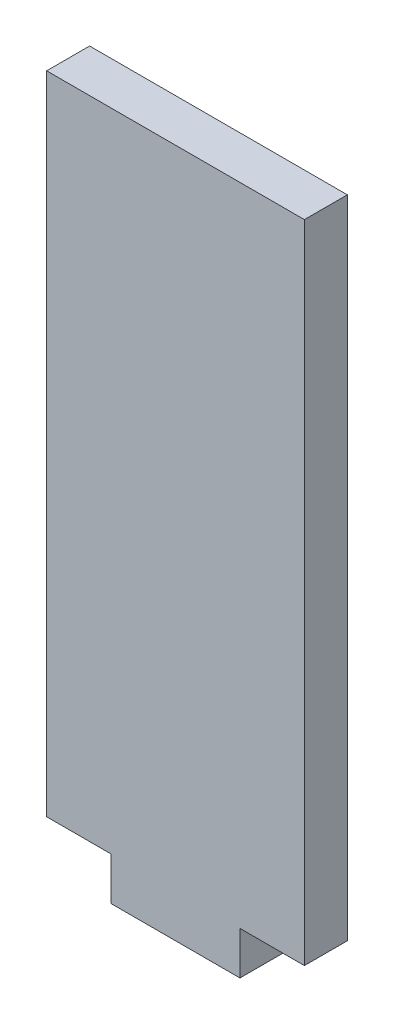
SolidWorks part; units mm, degrees
ref_plane "前视基准面" through (0, 0, 0) normal (0, 0, 1) x (1, 0, 0)
ref_plane "上视基准面" through (0, 0, 0) normal (0, 1, 0) x (1, 0, 0)
ref_plane "右视基准面" through (0, 0, 0) normal (1, 0, 0) x (0, 0, -1)
sketch "草图1" plane through (0, 0, 0) normal (0, 0, 1) x (1, 0, 0)
  line L0 (-6, 0) -> (-6, 15)
  line L1 (-6, 0) -> (-3, 0)
  line L3 (6, 0) -> (6, 15)
  line L4 (-3, 0) -> (-3, -2)
  line L6 (-3, -2) -> (3, -2)
  line L7 (3, 0) -> (3, -2)
  line L8 (-6, 15) -> (-6, 30.0788)
  line L9 (-6, 30.0788) -> (6, 30.0788)
  line L10 (6, 30.0788) -> (6, 15)
  line L11 (3, 0) -> (6, 0)
extrude "凸台-拉伸1" add sketch "草图1" along normal blind 2 contours L9 L10 L3 L11 L7 L6 L4 L1 L0 L8
sketch3d "3D草图1"
  spline S0 degree 3 poles (-3.7281, 8.6762, 2) (-3.7074, 8.1505, 2) (-3.6718, 7.893, 2) (-3.5521, 7.3881, 2) (-3.4667, 7.1383, 2) (-3.2501, 6.663, 2) (-3.1202, 6.4386, 2) (-2.8173, 6.0158, 2) (-2.6424, 5.8163, 2) (-2.2631, 5.461, 2) (-2.0574, 5.3028, 2) (-1.6134, 5.0266, 2) (-1.377, 4.9103, 2) (-0.8912, 4.7283, 2) (-0.6386, 4.661, 2) (-0.1203, 4.5774, 2) (0.1389, 4.5619, 2) (0.6578, 4.5819, 2) (0.9202, 4.6183, 2) (1.4267, 4.7412, 2) (1.6715, 4.827, 2) (2.1443, 5.0472, 2) (2.3719, 5.1823, 2) (2.7901, 5.4898, 2) (2.9836, 5.6635, 2) (3.3382, 6.0517, 2) (3.4938, 6.2605, 2) (3.7626, 6.7045, 2) (3.8768, 6.9427, 2) (4.0554, 7.4334, 2) (4.12, 7.6847, 2) (4.2005, 8.1988, 2) (4.2159, 8.4635, 2) (4.1957, 8.9828, 2) (4.1608, 9.2399, 2) (4.0405, 9.749, 2) (3.9551, 9.9981, 2) (3.7405, 10.4703, 2) (3.6101, 10.6966, 2) (3.3044, 11.1235, 2) (3.1331, 11.3188, 2) (2.7547, 11.674, 2) (2.545, 11.8354, 2) (2.1022, 12.1109, 2) (1.8696, 12.2256, 2) (1.3821, 12.4088, 2) (1.1259, 12.4769, 2) (0.6133, 12.5599, 2) (0.3541, 12.5761, 2) (-0.1701, 12.5562, 2) (-0.4295, 12.52, 2) (-0.9338, 12.3982, 2) (-1.1825, 12.3114, 2) (-1.6567, 12.0906, 2) (-1.88, 11.9582, 2) (-2.2993, 11.6505, 2) (-2.4966, 11.4732, 2) (-2.8474, 11.0893, 2) (-3.003, 10.8816, 2) (-3.2742, 10.4343, 2) (-3.388, 10.1968, 2) (-3.5658, 9.7094, 2) (-3.6314, 9.4564, 2) (-3.7128, 8.9374, 2) (-3.7281, 8.6762, 2) (-3.7074, 8.1505, 2) (-3.6718, 7.893, 2) knots -0.03125 -0.03125 0 0 0.03125 0.03125 0.0625 0.0625 0.09375 0.09375 0.125 0.125 0.15625 0.15625 0.1875 0.1875 0.21875 0.21875 0.25 0.25 0.28125 0.28125 0.3125 0.3125 0.34375 0.34375 0.375 0.375 0.40625 0.40625 0.4375 0.4375 0.46875 0.46875 0.5 0.5 0.53125 0.53125 0.5625 0.5625 0.59375 0.59375 0.625 0.625 0.65625 0.65625 0.6875 0.6875 0.71875 0.71875 0.75 0.75 0.78125 0.78125 0.8125 0.8125 0.84375 0.84375 0.875 0.875 0.90625 0.90625 0.9375 0.9375 0.96875 0.96875 1 1 1.03125 1.03125 1.0625 only from (-3.7177, 8.4134, 2) to (-3.7177, 8.4134, 2)
  spline S1 degree 3 poles (-3.7281, 8.6762, 2) (-3.7074, 8.1505, 2) (-3.6718, 7.893, 2) (-3.5521, 7.3881, 2) (-3.4667, 7.1383, 2) (-3.2501, 6.663, 2) (-3.1202, 6.4386, 2) (-2.8173, 6.0158, 2) (-2.6424, 5.8163, 2) (-2.2631, 5.461, 2) (-2.0574, 5.3028, 2) (-1.6134, 5.0266, 2) (-1.377, 4.9103, 2) (-0.8912, 4.7283, 2) (-0.6386, 4.661, 2) (-0.1203, 4.5774, 2) (0.1389, 4.5619, 2) (0.6578, 4.5819, 2) (0.9202, 4.6183, 2) (1.4267, 4.7412, 2) (1.6715, 4.827, 2) (2.1443, 5.0472, 2) (2.3719, 5.1823, 2) (2.7901, 5.4898, 2) (2.9836, 5.6635, 2) (3.3382, 6.0517, 2) (3.4938, 6.2605, 2) (3.7626, 6.7045, 2) (3.8768, 6.9427, 2) (4.0554, 7.4334, 2) (4.12, 7.6847, 2) (4.2005, 8.1988, 2) (4.2159, 8.4635, 2) (4.1957, 8.9828, 2) (4.1608, 9.2399, 2) (4.0405, 9.749, 2) (3.9551, 9.9981, 2) (3.7405, 10.4703, 2) (3.6101, 10.6966, 2) (3.3044, 11.1235, 2) (3.1331, 11.3188, 2) (2.7547, 11.674, 2) (2.545, 11.8354, 2) (2.1022, 12.1109, 2) (1.8696, 12.2256, 2) (1.3821, 12.4088, 2) (1.1259, 12.4769, 2) (0.6133, 12.5599, 2) (0.3541, 12.5761, 2) (-0.1701, 12.5562, 2) (-0.4295, 12.52, 2) (-0.9338, 12.3982, 2) (-1.1825, 12.3114, 2) (-1.6567, 12.0906, 2) (-1.88, 11.9582, 2) (-2.2993, 11.6505, 2) (-2.4966, 11.4732, 2) (-2.8474, 11.0893, 2) (-3.003, 10.8816, 2) (-3.2742, 10.4343, 2) (-3.388, 10.1968, 2) (-3.5658, 9.7094, 2) (-3.6314, 9.4564, 2) (-3.7128, 8.9374, 2) (-3.7281, 8.6762, 2) (-3.7074, 8.1505, 2) (-3.6718, 7.893, 2) knots -0.03125 -0.03125 0 0 0.03125 0.03125 0.0625 0.0625 0.09375 0.09375 0.125 0.125 0.15625 0.15625 0.1875 0.1875 0.21875 0.21875 0.25 0.25 0.28125 0.28125 0.3125 0.3125 0.34375 0.34375 0.375 0.375 0.40625 0.40625 0.4375 0.4375 0.46875 0.46875 0.5 0.5 0.53125 0.53125 0.5625 0.5625 0.59375 0.59375 0.625 0.625 0.65625 0.65625 0.6875 0.6875 0.71875 0.71875 0.75 0.75 0.78125 0.78125 0.8125 0.8125 0.84375 0.84375 0.875 0.875 0.90625 0.90625 0.9375 0.9375 0.96875 0.96875 1 1 1.03125 1.03125 1.0625 only from (-3.7177, 8.4134, 2) to (-3.7177, 8.4134, 2)
